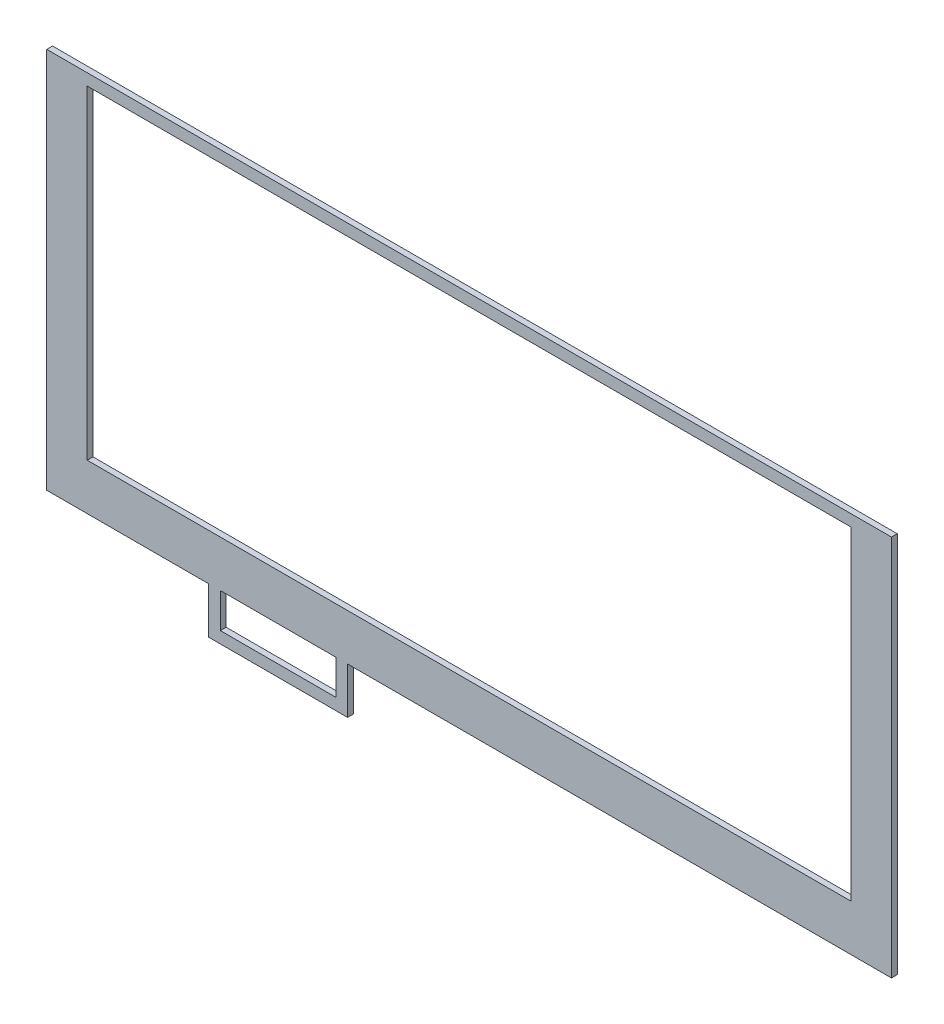
SolidWorks part; units mm, degrees
ref_plane "Alzado" through (0, 0, 0) normal (0, 0, 1) x (1, 0, 0)
ref_plane "Planta" through (0, 0, 0) normal (0, 1, 0) x (1, 0, 0)
ref_plane "Vista lateral" through (0, 0, 0) normal (1, 0, 0) x (0, 0, -1)
sketch "Croquis2" plane through (0, 0, 0) normal (0, 0, 1) x (1, 0, 0)
  line L1 (-365, -165) -> (365, -165)
  line L2 (-365, -165) -> (-365, 165)
  line L3 (-365, 165) -> (365, 165)
  line L4 (365, -165) -> (365, 165)
  line L5 (-365, -165) -> (365, 165) construction
  line L6 (-365, 165) -> (365, -165) construction
  point P0 (0, 0)
  dimension "D1" = 730
  dimension "D2" = 330
extrude "Saliente-Extruir2" add sketch "Croquis2" along normal blind 5
sketch "Croquis4" plane through (0, 0, 5) normal (0, 0, 1) x (1, 0, 0)
  line L0 (365, 165) -> (-365, 165) construction
  line L1 (330, 155) -> (-330, 155)
  line L2 (330, 155) -> (330, -125)
  line L3 (330, -125) -> (-330, -125)
  line L4 (-330, 155) -> (-330, -125)
  line L5 (365, -165) -> (365, 165) construction
  line L6 (-365, 165) -> (-365, -165) construction
  line L7 (-365, -165) -> (365, -165) construction
  dimension "D1" = 10
  dimension "D2" = 35
  dimension "D3" = 35
  dimension "D4" = 40
extrude "Cortar-Extruir1" cut sketch "Croquis4" against normal up to surface (5 mm away) up to face at (0, 0, 0)
sketch "Croquis5" plane through (0, 0, 5) normal (0, 0, 1) x (1, 0, 0)
  line L0 (-365, -165) -> (365, -165) construction
  line L1 (-225, -165) -> (-105, -165)
  line L2 (-225, -165) -> (-225, -205)
  line L3 (-225, -205) -> (-105, -205)
  line L4 (-105, -165) -> (-105, -205)
  line L5 (-365, 165) -> (-365, -165) construction
  line L7 (-215, -165) -> (-115, -165)
  line L8 (-215, -165) -> (-215, -195)
  line L9 (-215, -195) -> (-115, -195)
  line L10 (-115, -165) -> (-115, -195)
  line M8 (-365, -165) -> (365, -165)
  dimension "D1" = 140
  dimension "D2" = 10
  dimension "D3" = 10
extrude "Saliente-Extruir3" add sketch "Croquis5" against normal up to surface (5 mm away) contours L10 L9 L8 L2 L3 L4 M8 up to face at (0, 15, 0)
